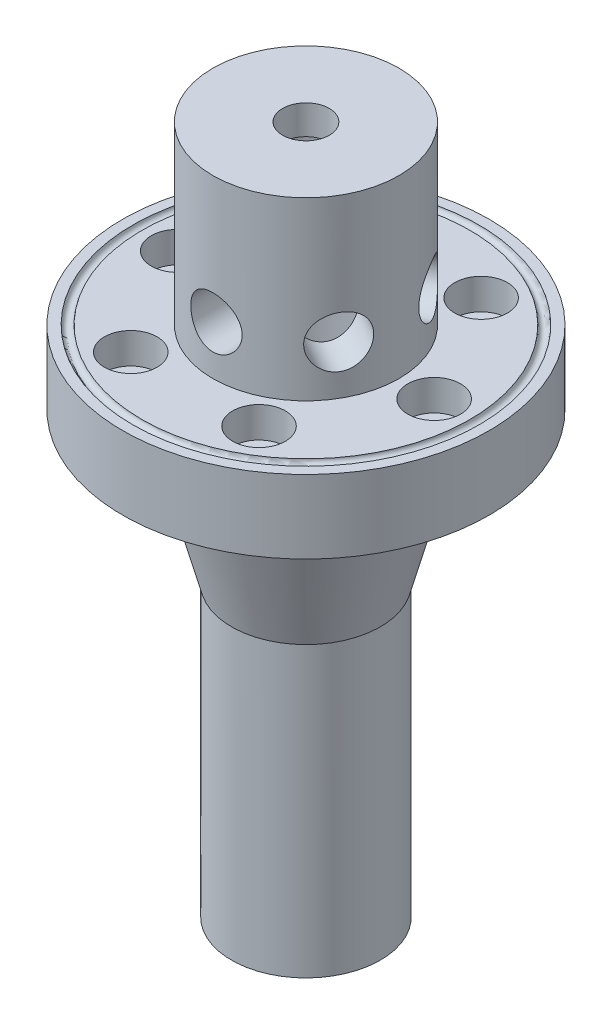
SolidWorks part; units mm, degrees
material "AISI 316 Annealed Stainless Steel Bar (SS)"
ref_plane "Front Plane" through (0, 0, 0) normal (0, 0, 1) x (1, 0, 0)
ref_plane "Top Plane" through (0, 0, 0) normal (0, 1, 0) x (1, 0, 0)
ref_plane "Right Plane" through (0, 0, 0) normal (1, 0, 0) x (0, 0, -1)
sketch "Sketch1" plane through (0, 0, 0) normal (1, 0, 0) x (0, 0, -1)
  line L0 (0, 0) -> (0, 97.3762) construction
  line L1 (0, 34) -> (12.7, 34)
  line L2 (12.7, 34) -> (12.7, 10)
  line L3 (12.7, 10) -> (25, 10)
  line L4 (25, 10) -> (25, 0)
  line L5 (25, 0) -> (15.68, 0)
  line L7 (0, 97.3762) -> (0, -129.0791) construction
  line L8 (0, -60) -> (0, 34)
  line L9 (10.16, -60) -> (0, -60)
  line L11 (10.16, 34) -> (10.16, 43.9813) construction
  line L12 (10.16, -60) -> (10.16, -20.6009)
  line L13 (15.68, 0) -> (10.16, -20.6009)
  dimension "D1" = 15
  dimension "D2" = 10.16
  dimension "D3" = 25
  dimension "D4" = 12.7
  dimension "D5" = 10
  dimension "D7" = 24
  dimension "D8" = 60
  dimension "D9" = 15.68
revolve "Revolve1" add sketch "Sketch1" angle 360 about L0
cosmetic thread "Cosmetic Thread1" parameters "D1"=10, "D2"=21.6205
sketch "Sketch5" plane through (0, -60, 0) normal (0, -1, 0) x (1, 0, 0)
  circle A1 centre (0, 0) radius 7.5
  dimension "D1" = 15
extrude "Cut-Extrude1" cut sketch "Sketch5" against normal blind 90
sketch "Sketch6" plane through (0, 0, 0) normal (0, 0, 1) x (1, 0, 0)
  circle A0 centre (0, 16.66) radius 3.5
  dimension "D1" = 7
extrude "Cut-Extrude2" cut sketch "Sketch6" against normal mid plane 40
pattern_circular "CirPattern1" count 6 over 360 about axis through (0, 34, 0) along (0, -1, 0) of "Cut-Extrude2"
sketch "Sketch9" plane through (0, 34, 0) normal (0, 1, 0) x (1, 0, 0)
  circle A0 centre (0, 0) radius 12.7
  circle A1 centre (0, 0) radius 25
  dimension "D1" = 25.4
  dimension "D2" = 50
sketch "Sketch10" plane through (0, 0, 0) normal (1, 0, 0) x (0, 0, -1)
  line L0 (0, 34) -> (0, 10) construction
  line L1 (25, 34) -> (-25, 34) construction
  line L2 (23.4, 10) -> (-23.4, 10) construction
  dimension "D1" = 24
sketch "Sketch11" plane through (0, 34, 0) normal (0, 1, 0) x (1, 0, 0)
  circle A0 centre (0, 0) radius 3.18
  dimension "D1" = 6.36
extrude "Cut-Extrude4" cut sketch "Sketch11" against normal through all
cosmetic thread "Cosmetic Thread2" parameters "D2"=7.9375
sketch "Sketch12" plane through (0, 10, 0) normal (0, 1, 0) x (1, 0, 0)
  circle A0 centre (0, 0) radius 17.5 construction
  dimension "D1" = 35
hole_wizard "Ø4.2 (4.2) Diameter Hole1" positions "Sketch13" profile "Sketch14" hole size "Ø4.2" standard "ANSI Metric" end condition through all
sketch "Sketch13" plane through (0, 10, 0) normal (0, 1, 0) x (1, 0, 0)
  circle A0 centre (0, 0) radius 17.5 construction
  point P0 (-17.5, 0)
sketch "Sketch14" plane through (-17.5, 10, 0) normal (1, 0, 0) x (0, 0, 1)
  line L0 (0, 0) -> (0, 70)
  line L1 (0, 70) -> (2.1, 70)
  line L2 (2.1, 70) -> (2.1, 0)
  line L5 (2.1, 0) -> (0, 0)
  line L11 (0, -6.35) -> (0, 107.95) construction
  dimension "Thru Hole Dia." = 4.2
  dimension "Thru Hole Depth" = 70
pattern_circular "CirPattern2" count 6 over 360 about axis through (0, 0, 0) along (0, 1, 0) of "Ø4.2 (4.2) Diameter Hole1"
sketch "Sketch15" plane through (0, 10, 0) normal (0, 1, 0) x (1, 0, 0)
  circle A0 centre (-17.5, 0) radius 3.6
  circle A1 centre (0, 0) radius 17.5 construction
  dimension "D1" = 7.2
extrude "Cut-Extrude5" cut sketch "Sketch15" against normal blind 4.2
pattern_circular "CirPattern3" count 6 over 360 about axis through (0, 0, 0) along (0, 1, 0) of "Cut-Extrude5"
sketch "Sketch16" plane through (0, 10, 0) normal (0, 1, 0) x (1, 0, 0)
  circle A1 centre (0, 0) radius 23
  dimension "D2" = 46
sweep "Cut-Sweep1" cut path "Sketch16" circular profile diameter 1.25 parameters "D3"=1.25
